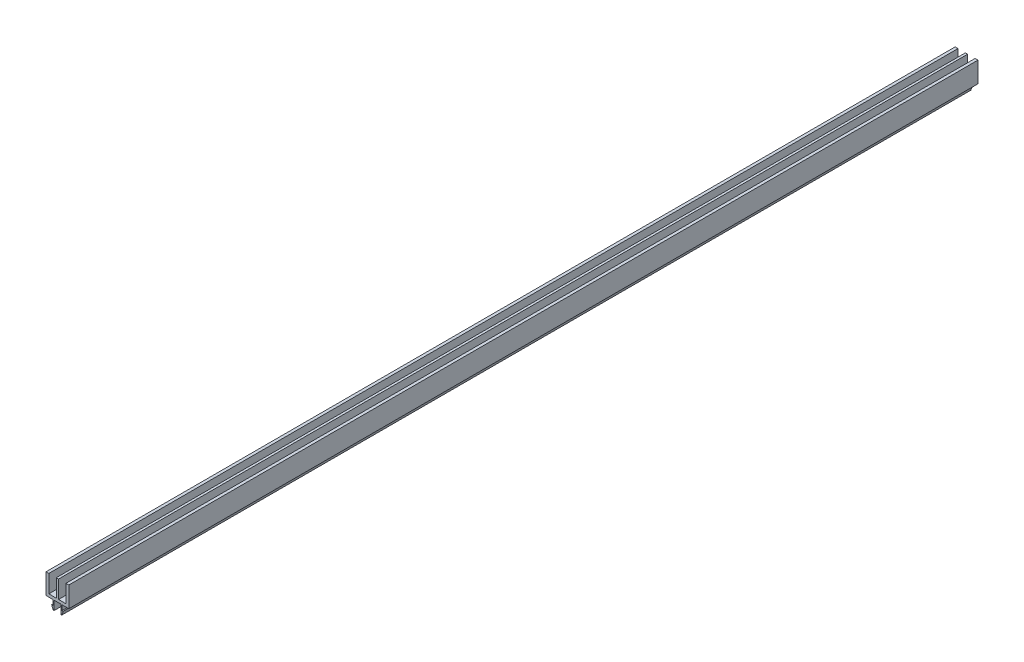
SolidWorks part; units mm, degrees
ref_plane "Plan de face" through (0, 0, 0) normal (0, 0, 1) x (1, 0, 0)
ref_plane "Plan de dessus" through (0, 0, 0) normal (0, 1, 0) x (1, 0, 0)
ref_plane "Plan de droite" through (0, 0, 0) normal (1, 0, 0) x (0, 0, -1)
ref_plane "Plan1" through (0, 0, 50) normal (0, 0, 1) x (1, 0, 0)
sketch "Esquisse1" plane through (0, 0, 50) normal (0, 0, 1) x (1, 0, 0)
  line L0 (-1, 2.5) -> (-7.5, 2.5)
  line L1 (-7.5, 2.5) -> (-7.5, 18)
  line L2 (-7.5, 18) -> (-10, 18)
  line L3 (-10, 18) -> (-10, 0)
  line L4 (-10, 0) -> (-4, 0)
  line L5 (-4, 0) -> (-4, -4.5)
  line L6 (-4, -4.5) -> (-5, -4.5)
  line L7 (-5, -4.5) -> (-3.75, -8)
  line L8 (-3.75, -8) -> (-3, -8)
  line L9 (-3, -8) -> (-3, 0)
  line L10 (-3, 0) -> (3, 0)
  line L11 (3, 0) -> (3, -8)
  line L12 (3, -8) -> (3.75, -8)
  line L13 (3.75, -8) -> (5, -4.5)
  line L14 (5, -4.5) -> (4, -4.5)
  line L15 (4, -4.5) -> (4, 0)
  line L16 (4, 0) -> (10, 0)
  line L17 (10, 0) -> (10, 18)
  line L18 (10, 18) -> (7.5, 18)
  line L19 (7.5, 18) -> (7.5, 2.5)
  line L20 (7.5, 2.5) -> (1, 2.5)
  line L21 (1, 2.5) -> (1, 18)
  line L22 (1, 18) -> (-1, 18)
  line L23 (-1, 18) -> (-1, 2.5)
extrude "Boss.-Extru.1" add sketch "Esquisse1" against normal blind 796
